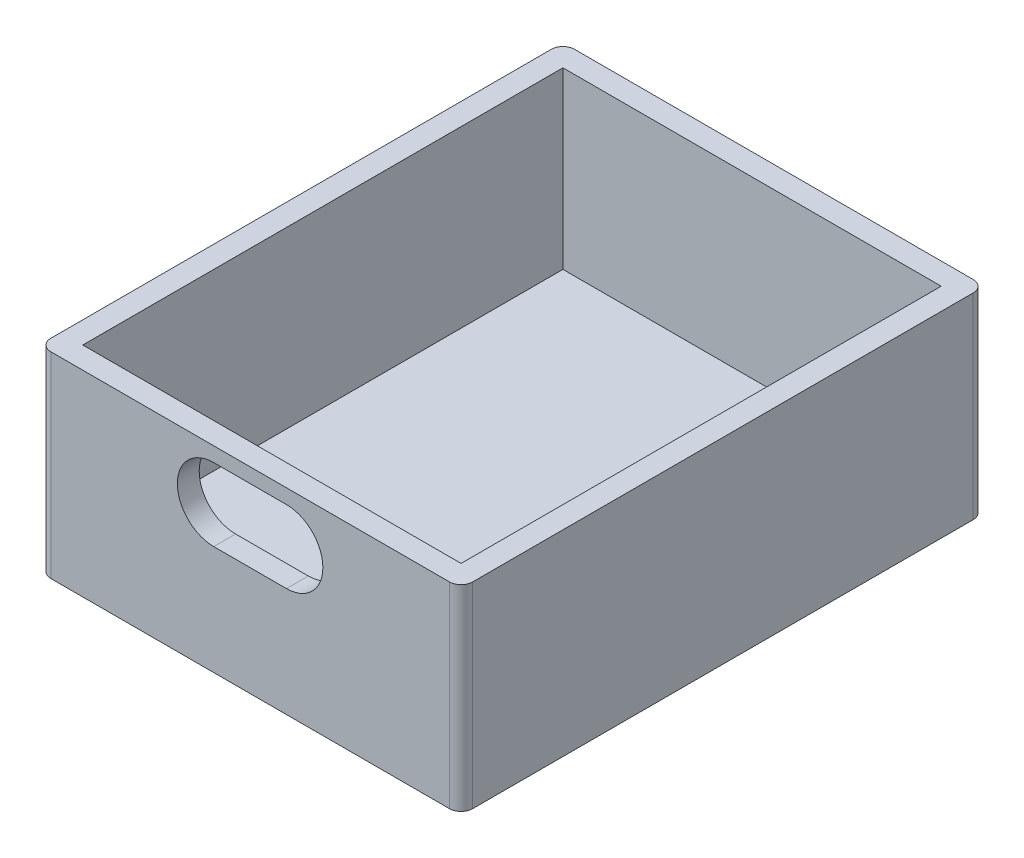
SolidWorks part; units mm, degrees
other "Markup1"
sketch "Sketch4" plane through (29, 0, 36) normal (0.3487, 0.4411, 0.8269) x (0.8274, -0.5594, -0.0504)
ref_plane "Front Plane" through (0, 0, 0) normal (0, 0, 1) x (1, 0, 0)
ref_plane "Top Plane" through (0, 0, 0) normal (0, 1, 0) x (1, 0, 0)
ref_plane "Right Plane" through (0, 0, 0) normal (1, 0, 0) x (0, 0, -1)
sketch "Sketch1" plane through (0, 0, 0) normal (0, 0, 1) x (1, 0, 0)
  line L1 (0, 0) -> (29, 0)
  line L2 (0, 0) -> (0, -13.5)
  line L3 (0, -13.5) -> (29, -13.5)
  line L4 (29, 0) -> (29, -13.5)
  dimension "D1" = 29
  dimension "D2" = 13.5
extrude "Boss-Extrude1" add sketch "Sketch1" along normal blind 36
sketch "Sketch2" plane through (0, 0, 0) normal (0, 1, 0) x (1, 0, 0)
  line L0 (0, -36) -> (0, 0) construction
  line L1 (1.5, -1.5) -> (27.5, -1.5)
  line L2 (1.5, -1.5) -> (1.5, -34.5)
  line L3 (1.5, -34.5) -> (27.5, -34.5)
  line L4 (27.5, -1.5) -> (27.5, -34.5)
  line L5 (29, -36) -> (29, 0) construction
  line L6 (29, 0) -> (0, 0) construction
  line L7 (29, -36) -> (0, -36) construction
  dimension "D1" = 1.5
  dimension "D2" = 1.5
  dimension "D3" = 1.5
  dimension "D4" = 1.5
extrude "Cut-Extrude1" cut sketch "Sketch2" against normal blind 12
sketch "Sketch3" plane through (0, 0, 36) normal (0, 0, 1) x (1, 0, 0)
  line L0 (12, -1) -> (17, -1)
  line L1 (12, -6) -> (17, -6)
  line L2 (0, -13.5) -> (29, -13.5) construction
  line L4 (29, -13.5) -> (29, 0) construction
  arc A3 (12, -6) -> (12, -1) centre (12, -3.5) cw
  arc A4 (17, -6) -> (17, -1) centre (17, -3.5) ccw
  dimension "D1" = 2.5
  dimension "D4" = 2.5
  dimension "D6" = 2.5
  dimension "D2" = 5
  dimension "D3" = 5
  dimension "D5" = 7.5
  dimension "D7" = 5
  dimension "D8" = 12
extrude "Cut-Extrude2" cut sketch "Sketch3" against normal up to surface (1.5 mm away) contours A3 L0 A4 L1 up to face at (14.5, -6, 34.5)
fillet "Fillet1" radius 0.8 4 edges at (0, -6.75, 36) (0, -6.75, 0) (29, -6.75, 0) (29, -6.75, 36)
